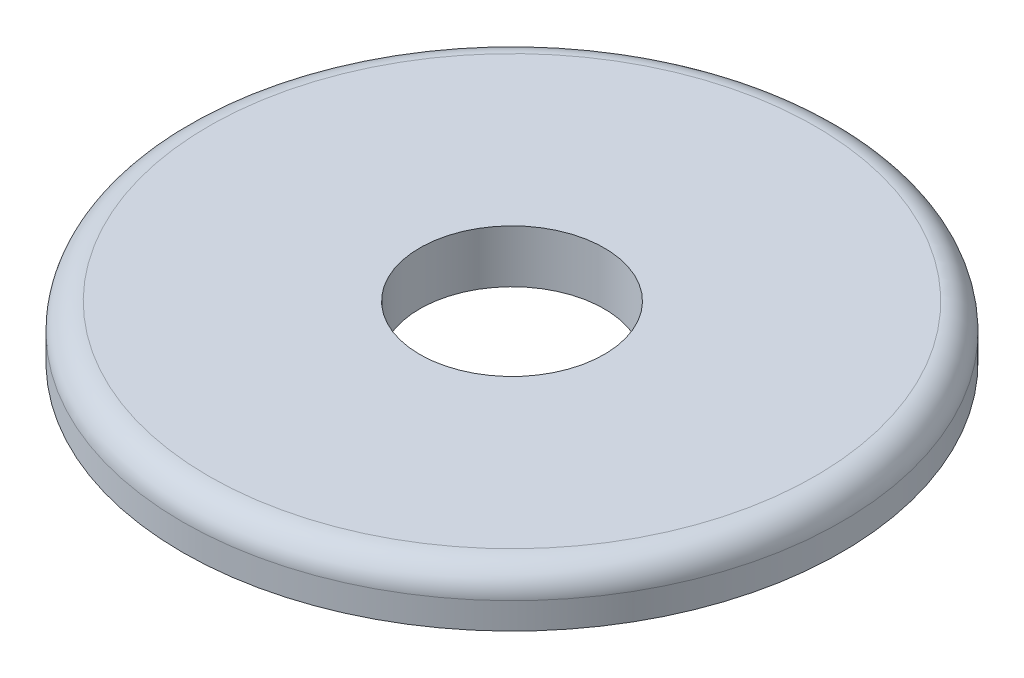
SolidWorks part; units mm, degrees
ref_plane "Front Plane" through (0, 0, 0) normal (0, 0, 1) x (1, 0, 0)
ref_plane "Top Plane" through (0, 0, 0) normal (0, 1, 0) x (1, 0, 0)
ref_plane "Right Plane" through (0, 0, 0) normal (1, 0, 0) x (0, 0, -1)
sketch "Sketch1" plane through (0, 0, 0) normal (0, 1, 0) x (1, 0, 0)
  circle A0 centre (0, 0) radius 3.5
  circle A1 centre (0, 0) radius 12.5
extrude "Boss-Extrude1" add sketch "Sketch1" along normal blind 2
fillet "Fillet1" radius 1 1 edges at (0, 2, 12.5)
